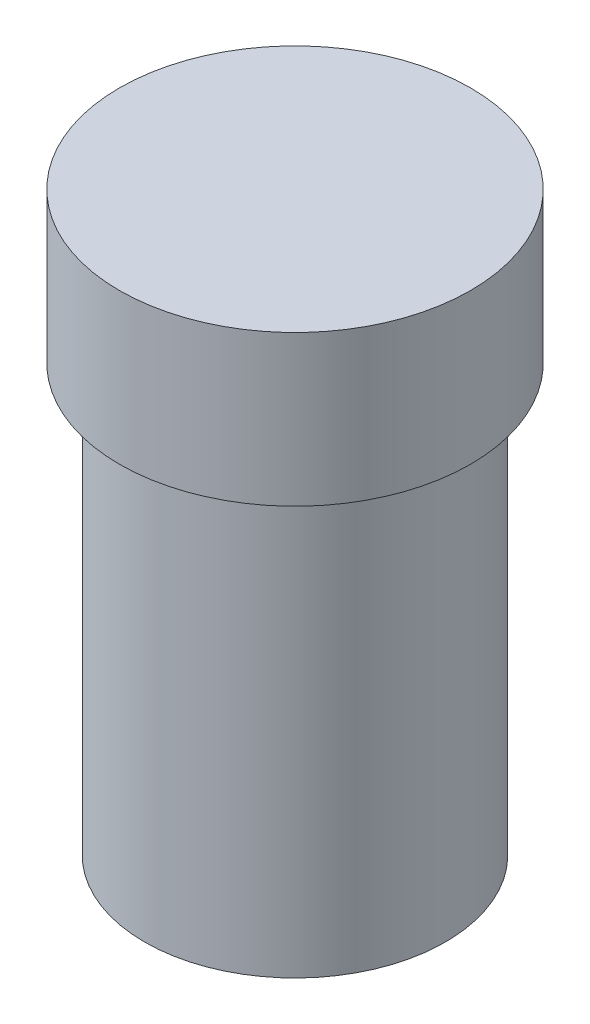
SolidWorks part; units mm, degrees
ref_plane "Front Plane" through (0, 0, 0) normal (0, 0, 1) x (1, 0, 0)
ref_plane "Top Plane" through (0, 0, 0) normal (0, 1, 0) x (1, 0, 0)
ref_plane "Right Plane" through (0, 0, 0) normal (1, 0, 0) x (0, 0, -1)
sketch "Sketch1" plane through (0, 0, 0) normal (0, 1, 0) x (1, 0, 0)
  circle A0 centre (0, 0) radius 7
  dimension "D1" = 14
extrude "Boss-Extrude1" add sketch "Sketch1" along normal blind 23
sketch "Sketch2" plane through (0, 0, 0) normal (0, -1, 0) x (1, 0, 0)
  circle A0 centre (0, 0) radius 6
  circle A1 centre (0, 0) radius 7
  circle A2 centre (0, 0) radius 7
  dimension "D2" = 12
  dimension "D1" = 0
extrude "Cut-Extrude1" cut sketch "Sketch2" against normal blind 17
